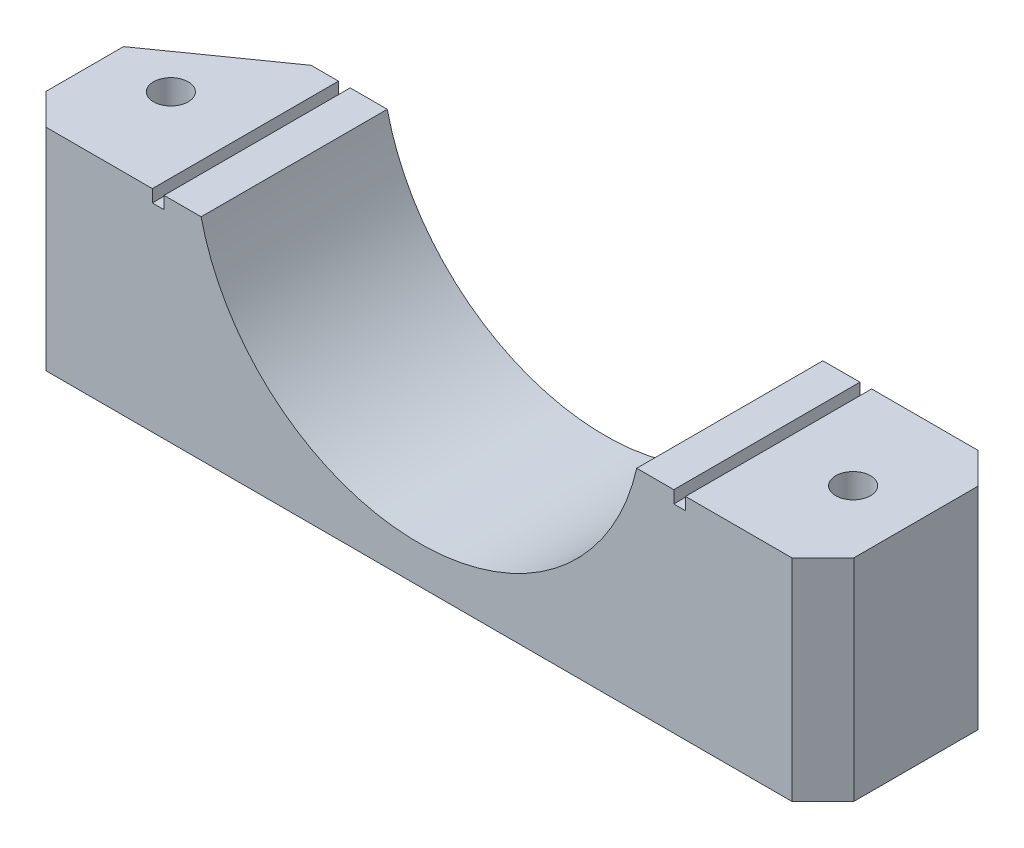
SolidWorks part; units mm, degrees
ref_plane "Front Plane" through (0, 0, 0) normal (0, 0, 1) x (1, 0, 0)
ref_plane "Top Plane" through (0, 0, 0) normal (0, 1, 0) x (1, 0, 0)
ref_plane "Right Plane" through (0, 0, 0) normal (1, 0, 0) x (0, 0, -1)
sketch "Sketch1" plane through (0, 0, 0) normal (0, 0, 1) x (1, 0, 0)
  line L0 (-17.5499, -4) -> (-32.5499, -4)
  line L1 (-32.5499, -4) -> (-32.5499, -21)
  line L2 (-32.5499, -21) -> (32.5499, -21)
  line L3 (32.5499, -21) -> (32.5499, -4)
  line L4 (32.5499, -4) -> (17.5499, -4)
  arc A0 (-17.5499, -4) -> (17.5499, -4) centre (0, 0) ccw
  dimension "D1" = 18
  dimension "D2" = 15
  dimension "D3" = 15
  dimension "D4" = 21
  dimension "D5" = 4
extrude "Boss-Extrude1" add sketch "Sketch1" along normal blind 15 contours L4 A0 L0 L1 L2 L3
chamfer "Chamfer1" distance 2.5 3 edges at (32.5499, -12.5, 0) (32.5499, -12.5, 15) (-32.5499, -12.5, 15)
sketch "Sketch2" plane through (0, -4, 0) normal (0, 1, 0) x (1, 0, 0)
  line L0 (0, -8.25) -> (0, 8.25) construction
  circle A0 centre (27.4886, -7.5) radius 1.4
  circle A1 centre (-27.4886, -7.5) radius 1.4
  dimension "D1" = 2.8
extrude "Cut-Extrude1" cut sketch "Sketch2" against normal through all
sketch "Sketch3" plane through (0, -4, 0) normal (0, 1, 0) x (1, 0, 0)
  line L0 (-17.5499, 0) -> (-32.5499, 0) construction
  line L1 (-21.4797, 0) -> (-20.5371, 0)
  line L2 (-21.4797, 0) -> (-21.4797, -15)
  line L3 (-21.4797, -15) -> (-20.5371, -15)
  line L4 (-20.5371, 0) -> (-20.5371, -15)
  line L5 (-17.5499, -15) -> (-30.0499, -15) construction
extrude "Cut-Extrude2" cut sketch "Sketch3" against normal blind 1 contours L2 L1 L4 L3
mirror "Mirror1" about plane through (0, 0, 0) normal (1, 0, 0) of "Cut-Extrude2"
sketch "Sketch4" plane through (0, -21, 0) normal (0, -1, 0) x (1, 0, 0)
  line L0 (-23.6831, 0) -> (-32.5499, 6.25)
  line L1 (-32.5499, 0) -> (30.0499, 0) construction
  line L2 (-32.5499, 12.5) -> (-32.5499, 0) construction
  line L3 (-32.5499, 6.25) -> (-32.5499, 0)
  line L4 (-32.5499, 0) -> (-23.6831, 0)
  point P6 (-23.6831, 0)
extrude "Cut-Extrude3" cut sketch "Sketch4" against normal blind 25
